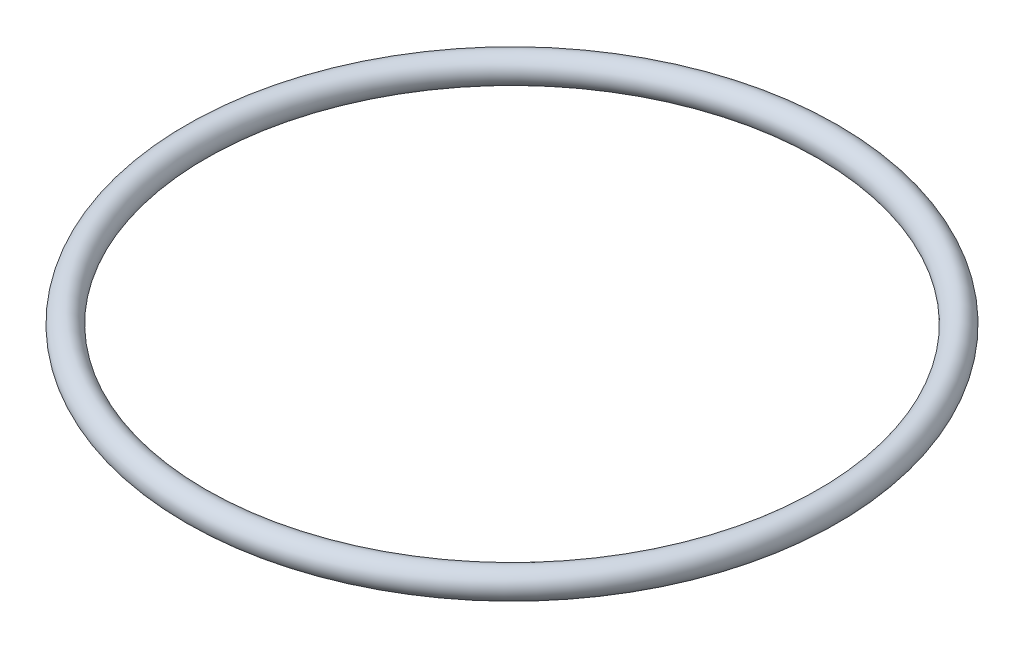
SolidWorks part; units mm, degrees
ref_plane "Front Plane" through (0, 0, 0) normal (0, 0, 1) x (1, 0, 0)
ref_plane "Top Plane" through (0, 0, 0) normal (0, 1, 0) x (1, 0, 0)
ref_plane "Right Plane" through (0, 0, 0) normal (1, 0, 0) x (0, 0, -1)
sketch "Sketch1" plane through (0, 0, 0) normal (0, 0, 1) x (1, 0, 0)
  line L0 (0, 3.6105) -> (0, -3.6105) construction
  line L1 (0, 0) -> (-18.307, 0) construction
  circle A0 centre (-18.307, 0) radius 0.7937
  point P4 (0, 0)
  dimension "D1" = 1.5875
  dimension "D2" = 18.307
revolve "Revolve1" add sketch "Sketch1" angle 360 about L0
